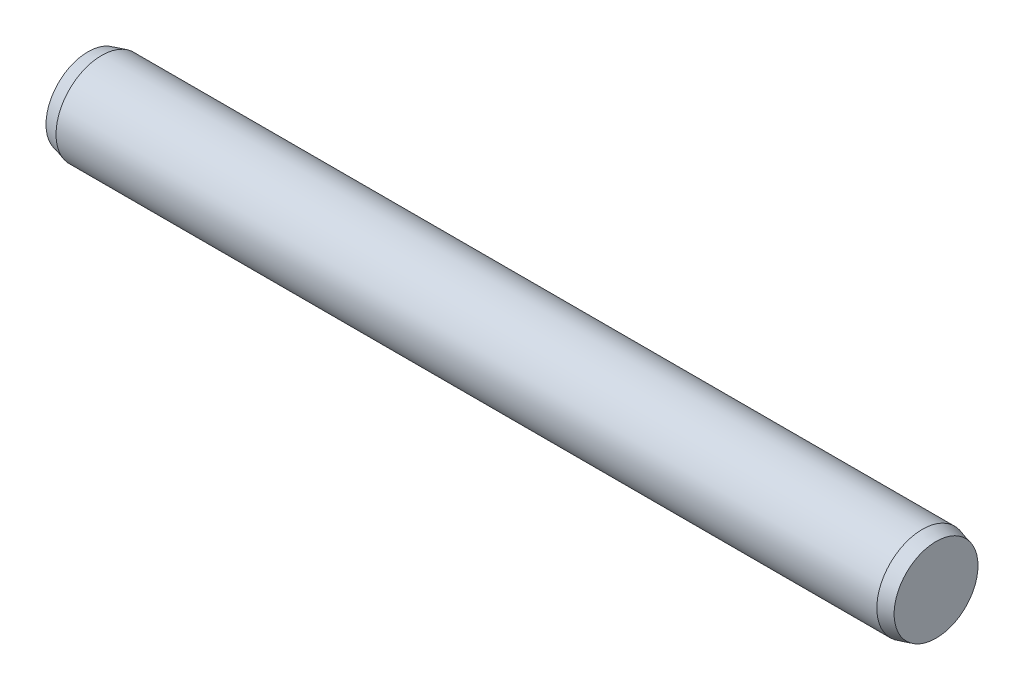
SolidWorks part; units mm, degrees
ref_plane "Front Plane" through (0, 0, 0) normal (0, 0, 1) x (1, 0, 0)
ref_plane "Top Plane" through (0, 0, 0) normal (0, 1, 0) x (1, 0, 0)
ref_plane "Right Plane" through (0, 0, 0) normal (1, 0, 0) x (0, 0, -1)
sketch "Sketch1" plane through (0, 0, 0) normal (0, 0, 1) x (1, 0, 0)
  line L0 (-9, 0) -> (9, 0) construction
  line L1 (9, 1) -> (9, -1) construction
  line L2 (-9, 1) -> (-9, -1) construction
  line L3 (9.3, 1) -> (9.3, -1) construction
  line L4 (-9.3, 1) -> (-9.3, -1) construction
  line L5 (-9, 0) -> (-9.3, 0) construction
  line L6 (9, 0) -> (9.3, 0) construction
  dimension "D1" = 0.3
  dimension "Dia" = 2
  dimension "Length" = 18
  dimension "C" = 0.3
sketch "Sketch2" plane through (0, 0, 0) normal (1, 0, 0) x (0, 0, -1)
  circle A0 centre (0, 0) radius 1
extrude "Extrude1" add sketch "Sketch2" against normal up to vertex (9 mm away) and the other way up to vertex (9 mm away) up to point (-9, 1, 0) other way up to point (9, 1, 0)
sketch "Sketch3" plane through (9, 0, 0) normal (1, 0, 0) x (0, 0, -1)
  circle A1 centre (0, 0) radius 1
  circle A2 centre (0, 0) radius 1
  dimension "D1" = 0
extrude "Extrude2" add sketch "Sketch3" along normal up to vertex (0.3 mm away) draft 15 up to point (9.3, 0, 0)
sketch "Sketch4" plane through (-9, 0, 0) normal (-1, 0, 0) x (0, 0, 1)
  circle A1 centre (0, 0) radius 1
  circle A2 centre (0, 0) radius 1
  dimension "D1" = 0
extrude "Extrude3" add sketch "Sketch4" along normal up to vertex (0.3 mm away) draft 15 up to point (-9.3, 0, 0)
equation "\"D1@Sketch1\" = \"C@Sketch1\""
